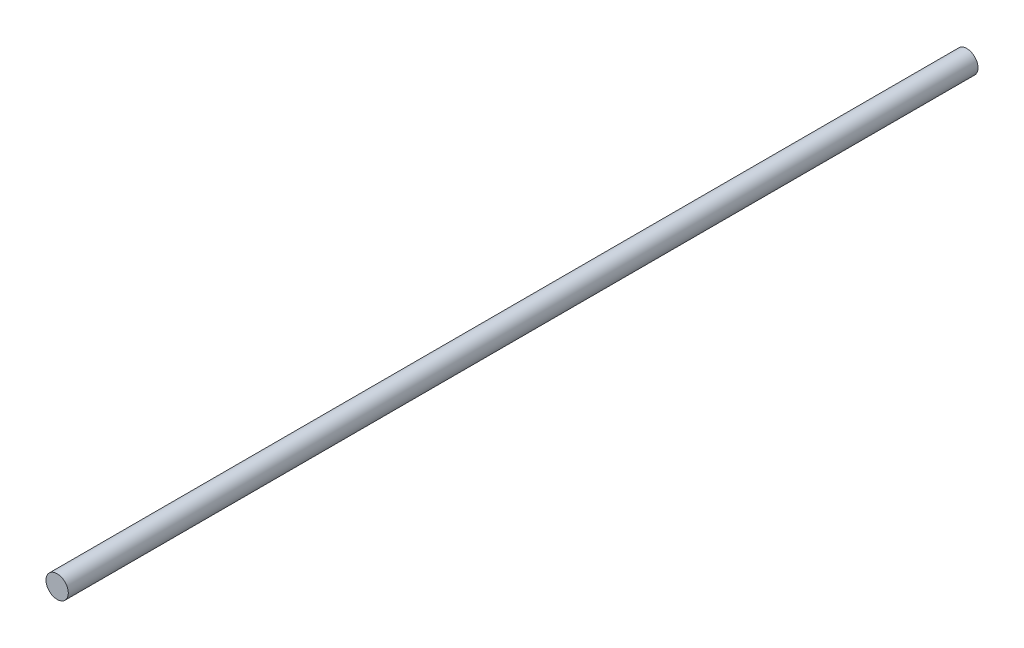
SolidWorks part; units mm, degrees
ref_plane "Alzado" through (0, 0, 0) normal (0, 0, 1) x (1, 0, 0)
ref_plane "Planta" through (0, 0, 0) normal (0, 1, 0) x (1, 0, 0)
ref_plane "Vista lateral" through (0, 0, 0) normal (1, 0, 0) x (0, 0, -1)
sketch "Croquis1" plane through (0, 0, 0) normal (0, 0, 1) x (1, 0, 0)
  circle A0 centre (0, 0) radius 4
extrude "Saliente-Extruir1" add sketch "Croquis1" along normal blind 326
